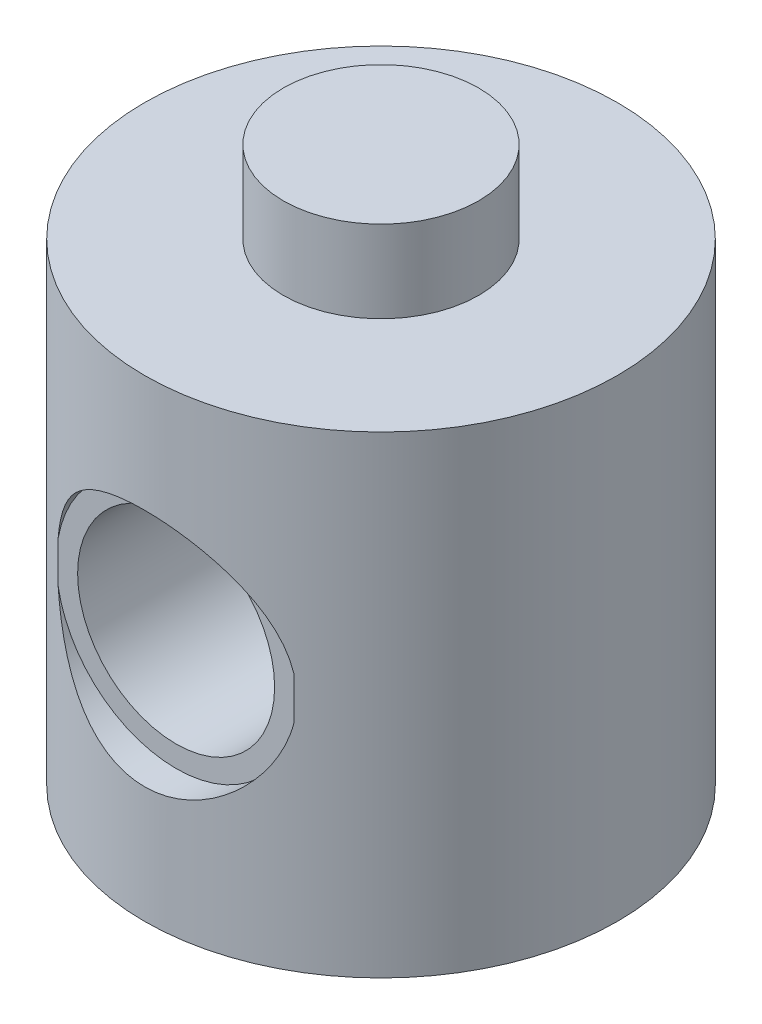
SolidWorks part; units mm, degrees
ref_plane "Front Plane" through (0, 0, 0) normal (0, 0, 1) x (1, 0, 0)
ref_plane "Top Plane" through (0, 0, 0) normal (0, 1, 0) x (1, 0, 0)
ref_plane "Right Plane" through (0, 0, 0) normal (1, 0, 0) x (0, 0, -1)
sketch "Sketch4" plane through (0, 0, 0) normal (0, 0, 1) x (1, 0, 0)
  line L0 (0, 7.8307) -> (0, -33.9271) construction
  line L1 (0, 0) -> (3.937, 0)
  line L2 (3.937, 0) -> (3.937, -3.302)
  line L3 (3.937, -3.302) -> (9.525, -3.302)
  line L4 (9.525, -3.302) -> (9.525, -22.352)
  line L5 (9.525, -22.352) -> (3.937, -22.352)
  line L6 (3.937, -22.352) -> (3.937, -25.654)
  line L7 (3.937, -25.654) -> (0, -25.654)
  line L8 (0, -25.654) -> (0, 0)
  dimension "D1" = 3.937
  dimension "D2" = 5.588
  dimension "D3" = 25.654
  dimension "D4" = 19.05
revolve "Revolve1" add sketch "Sketch4" angle 360 about L8
ref_plane "Plane2" through (0, 0, 9.525) normal (0, 0, 1) x (1, 0, 0)
sketch "Sketch9" plane through (0, 0, 9.525) normal (0, 0, 1) x (1, 0, 0)
  line L0 (9.525, -22.352) -> (-9.525, -3.302) construction
  line L1 (-9.525, -22.352) -> (9.525, -3.302) construction
  circle A0 centre (0, -12.827) radius 4.826
  dimension "D1" = 9.652
extrude "Cut-Extrude1" cut sketch "Sketch9" against normal blind 1.27
hole_wizard "3/8-16 Tapped Hole2" positions "3DSketch3" profile "Sketch10" tap size "3/8-16" standard "ANSI Inch" end condition through all
sketch3d "3DSketch3"
  point P0 (29.6788, -9.2846, 0)
  point P2 (0, -12.827, 9.525)
  point P5 (0, -12.827, 9.525)
  point P7 (0, -12.827, 8.255)
  point P10 (0, 0, 0)
sketch "Sketch10" plane through (0, -12.827, 8.255) normal (1, 0, 0) x (0, -1, 0)
  line L0 (0, 0) -> (0, 17.78)
  line L1 (0, 17.78) -> (3.9687, 17.78)
  line L2 (3.9687, 17.78) -> (3.9687, 0)
  line L5 (3.9687, 0) -> (0, 0)
  line L11 (0, -6.35) -> (0, 107.95) construction
  dimension "Thru Tap Drill Dia." = 7.9375
  dimension "Thru Tap Drill Depth" = 17.78
cosmetic thread "Hole Thread2" parameters "D2"=9.525
cosmetic thread "Hole Thread3" parameters "D2"=9.525
cosmetic thread "Hole Thread4" parameters "D2"=9.525
cosmetic thread "Hole Thread5" parameters "D2"=9.525
cosmetic thread "Cosmetic Thread1" parameters "D1"=3.048, "D2"=9.525
